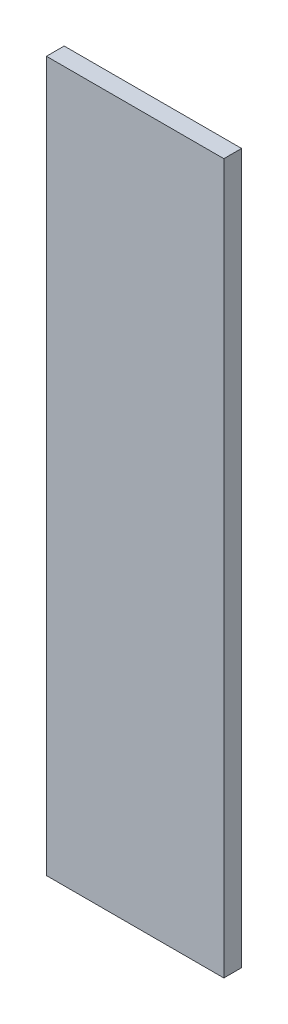
SolidWorks part; units mm, degrees
ref_plane "前视" through (0, 0, 0) normal (0, 0, 1) x (1, 0, 0)
ref_plane "上视" through (0, 0, 0) normal (0, 1, 0) x (1, 0, 0)
ref_plane "右视" through (0, 0, 0) normal (1, 0, 0) x (0, 0, -1)
sketch "草图1" plane through (0, 0, 0) normal (0, 0, 1) x (1, 0, 0)
  line L0 (40, 352.4218) -> (40, -138.3119) construction
  line L1 (0, 0) -> (80, 0)
  line L2 (0, 0) -> (0, 320)
  line L3 (0, 320) -> (80, 320)
  line L4 (80, 0) -> (80, 320)
  dimension "D1" = 320
  dimension "D2" = 80
extrude "基体-拉伸" add sketch "草图1" along normal blind 8
